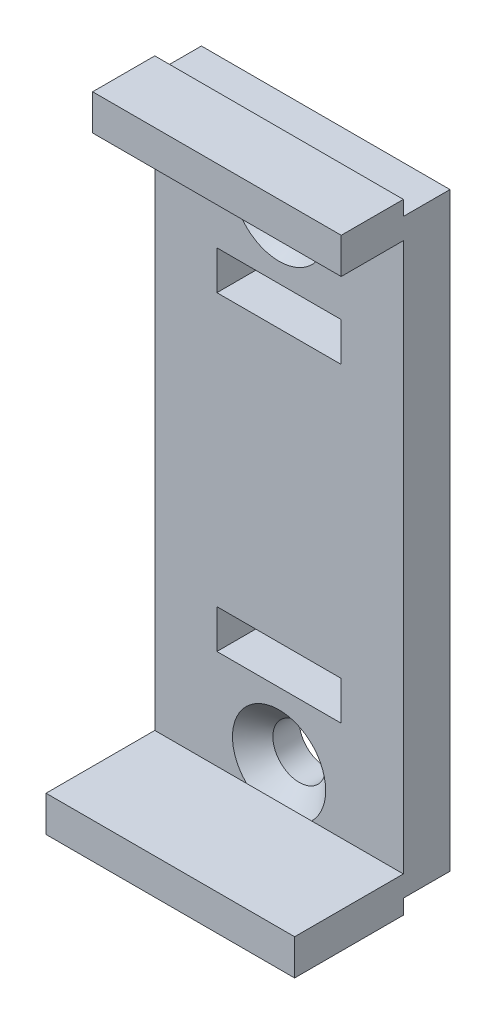
SolidWorks part; units mm, degrees
ref_plane "前视基准面" through (0, 0, 0) normal (0, 0, 1) x (1, 0, 0)
ref_plane "上视基准面" through (0, 0, 0) normal (0, 1, 0) x (1, 0, 0)
ref_plane "右视基准面" through (0, 0, 0) normal (1, 0, 0) x (0, 0, -1)
other "Configuration Table"
sketch "Sketch_Camera_seat" plane through (0, 0, 0) normal (0, 0, 1) x (1, 0, 0)
  line L0 (8, -19) -> (8, 19)
  line L1 (8, 19) -> (-8, 19)
  line L2 (-8, 19) -> (-8, -19)
  line L3 (-8, -19) -> (8, -19)
extrude "Camera_seat" add sketch "Sketch_Camera_seat" along normal blind 3 from offset 0
sketch "Sketch_Front_lip" plane through (0, 0, 0) normal (0, 0, 1) x (1, 0, 0)
  line L0 (8, -19.95) -> (8, -17.65)
  line L1 (8, -17.65) -> (-8, -17.65)
  line L2 (-8, -17.65) -> (-8, -19.95)
  line L3 (-8, -19.95) -> (8, -19.95)
extrude "Front_lip" add sketch "Sketch_Front_lip" along normal blind 7 from offset 3
sketch "Sketch_Rear_lip" plane through (0, 0, 0) normal (0, 0, 1) x (1, 0, 0)
  line L0 (8, 17.65) -> (8, 19.95)
  line L1 (8, 19.95) -> (-8, 19.95)
  line L2 (-8, 19.95) -> (-8, 17.65)
  line L3 (-8, 17.65) -> (8, 17.65)
extrude "Rear_lip" add sketch "Sketch_Rear_lip" along normal blind 4 from offset 3
sketch "Sketch_Strap_slots" plane through (0, 0, 0) normal (0, 0, 1) x (1, 0, 0)
  line L0 (-4, -11.25) -> (-4, -8.75)
  line L1 (-4, -8.75) -> (4, -8.75)
  line L2 (4, -8.75) -> (4, -11.25)
  line L3 (4, -11.25) -> (-4, -11.25)
  line L4 (-4, 8.75) -> (-4, 11.25)
  line L5 (-4, 11.25) -> (4, 11.25)
  line L6 (4, 11.25) -> (4, 8.75)
  line L7 (4, 8.75) -> (-4, 8.75)
extrude "Strap_slots" cut sketch "Sketch_Strap_slots" along normal blind 5 from offset 1
sketch "Sketch_M3_through" plane through (0, 0, 0) normal (0, 0, 1) x (1, 0, 0)
  circle A0 centre (0, -15.5) radius 1.7
  circle A1 centre (0, 15.5) radius 1.7
  dimension "D1" = 3.4
  dimension "D3" = 3.4
  dimension "D2" = 15.5
  dimension "D4" = 15.5
extrude "M3_through" cut sketch "Sketch_M3_through" along normal blind 5 from offset 1
sketch "Sketch_Flat_head_90deg" plane through (0, 0, 0) normal (0, 0, 1) x (1, 0, 0)
  circle A0 centre (0, -15.5) radius 1.5
  circle A1 centre (0, 15.5) radius 1.5
  dimension "D1" = 3
  dimension "D3" = 3
  dimension "D2" = 15.5
  dimension "D4" = 15.5
extrude "Flat_head_90deg" cut sketch "Sketch_Flat_head_90deg" along normal blind 1.5 draft 45 from offset 1.5
